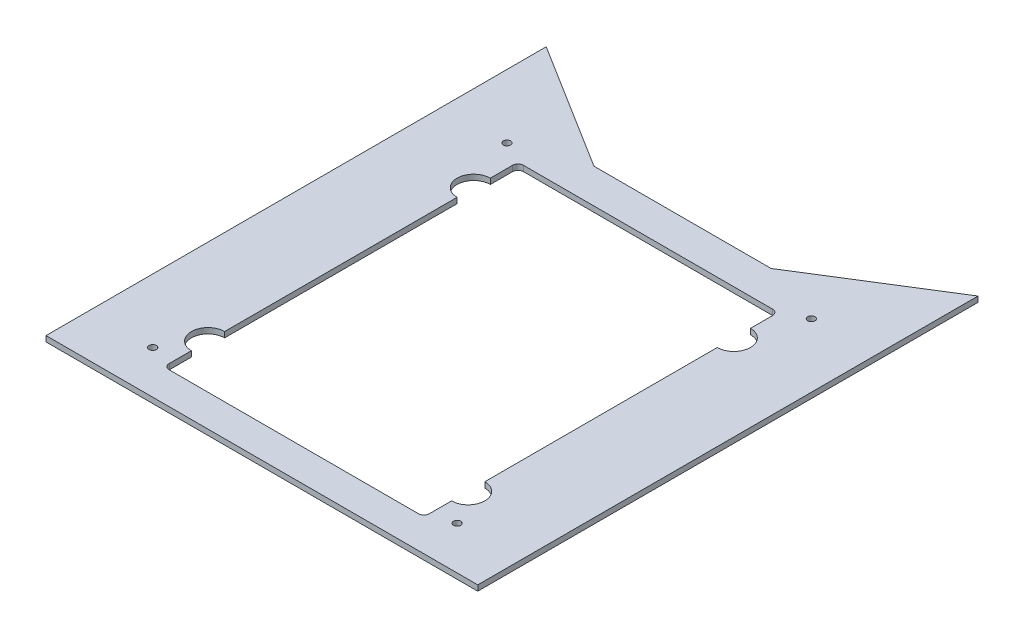
SolidWorks part; units mm, degrees
material "Balsa"
ref_plane "Front Plane" through (0, 0, 0) normal (0, 0, 1) x (1, 0, 0)
ref_plane "Top Plane" through (0, 0, 0) normal (0, 1, 0) x (1, 0, 0)
ref_plane "Right Plane" through (0, 0, 0) normal (1, 0, 0) x (0, 0, -1)
sketch "Sketch1" plane through (0, 0, 0) normal (0, 1, 0) x (1, 0, 0)
  line L17 (265.3132, -148.5502) -> (201.8132, -148.5502) construction
  line L18 (265.3132, -148.5502) -> (265.3132, -339.0502) construction
  line L19 (265.3132, -339.0502) -> (201.8132, -339.0502) construction
  line L20 (201.8132, -148.5502) -> (201.8132, -339.0502) construction
  line L21 (-153.7868, -148.5502) -> (-153.7868, -339.0502) construction
  line L22 (-217.2868, -339.0502) -> (-153.7868, -339.0502) construction
  line L23 (-217.2868, -148.5502) -> (-217.2868, -339.0502) construction
  line L24 (-217.2868, -148.5502) -> (-153.7868, -148.5502) construction
  line L25 (-242.6868, -133.4325) -> (-242.6868, -385.4912) construction
  line L26 (-191.8868, -438.1717) -> (-242.6868, -387.3717) construction
  line L27 (-191.8868, -438.1717) -> (239.9132, -438.1717) construction
  line L28 (239.9132, -438.1717) -> (290.7132, -387.3717) construction
  line L29 (290.7132, -387.3717) -> (290.7132, -133.3717) construction
  line L30 (290.7132, -133.3717) -> (176.4132, -82.5717) construction
  line L31 (176.4132, -82.5717) -> (176.4132, -133.3717) construction
  line L32 (176.4132, -133.3717) -> (74.8132, -196.8717) construction
  line L33 (74.8132, -196.8717) -> (-26.7868, -196.8717) construction
  line L34 (-128.3868, -133.3717) -> (-26.7868, -196.8717) construction
  line L35 (-128.3868, -82.5717) -> (-128.3868, -133.3717) construction
  line L36 (-242.6868, -133.3717) -> (-128.3868, -82.5717) construction
  line L37 (265.3132, -148.5502) -> (201.8132, -148.5502)
  line L38 (265.3132, -148.5502) -> (265.3132, -339.0502)
  line L39 (265.3132, -339.0502) -> (201.8132, -339.0502)
  line L40 (201.8132, -148.5502) -> (201.8132, -339.0502)
  line L41 (-153.7868, -148.5502) -> (-153.7868, -339.0502)
  line L42 (-217.2868, -339.0502) -> (-153.7868, -339.0502)
  line L43 (-217.2868, -148.5502) -> (-217.2868, -339.0502)
  line L44 (-217.2868, -148.5502) -> (-153.7868, -148.5502)
  line L45 (-242.6868, -133.4325) -> (-242.6868, -385.4912)
  line L46 (-191.8868, -438.1717) -> (-242.6868, -387.3717)
  line L47 (-191.8868, -438.1717) -> (239.9132, -438.1717)
  line L48 (239.9132, -438.1717) -> (290.7132, -387.3717)
  line L49 (290.7132, -387.3717) -> (290.7132, -133.3717)
  line L50 (290.7132, -133.3717) -> (176.4132, -82.5717)
  line L51 (176.4132, -82.5717) -> (176.4132, -133.3717)
  line L52 (176.4132, -133.3717) -> (74.8132, -196.8717)
  line L53 (74.8132, -196.8717) -> (-26.7868, -196.8717)
  line L54 (-128.3868, -133.3717) -> (-26.7868, -196.8717)
  line L55 (-128.3868, -82.5717) -> (-128.3868, -133.3717)
  line L56 (-242.6868, -133.3717) -> (-128.3868, -82.5717)
  line L57 (-242.6868, -133.4325) -> (-242.6868, -133.3717)
  line L58 (-242.6868, -385.4912) -> (-242.6868, -387.3717)
extrude "Boss-Extrude1" add sketch "Sketch1" along normal blind 3.175
sketch "Sketch3" plane through (0, 0, 0) normal (0, 1, 0) x (1, 0, 0)
  line L1 (-143.449, -203.465) -> (-143.449, -284.1354) construction
  line L2 (-143.449, -243.8002) -> (24.0132, -243.8002) construction
  line L3 (-191.8868, -438.1717) -> (239.9132, -438.1717) construction
  line L4 (-217.2868, -339.0502) -> (-153.7868, -339.0502) construction
  point P7 (24.0132, -438.1717)
  line B0 (24.0132, -13.4981) -> (24.0132, 49986.5019) construction
  circle B1 centre (-114.2782, -270.1255) radius 2.0828
  circle B2 centre (-143.449, -284.1354) radius 2.0828
  circle B3 centre (-114.2782, -217.4749) radius 2.0828
  circle B4 centre (-143.449, -203.465) radius 2.0828
  circle B5 centre (191.4754, -284.1354) radius 2.0828
  circle B6 centre (162.3046, -270.1255) radius 2.0828
  circle B7 centre (162.3046, -217.4749) radius 2.0828
  circle B8 centre (191.4754, -203.465) radius 2.0828
  dimension "D1" = 95.25
sketch_block_instance "motor_mount_pattern-1"
sketch_block "motor_mount_pattern"
extrude "Cut-Extrude2" cut sketch "Sketch3" along normal through all
sketch "Sketch4" plane through (0, 0, 0) normal (0, 1, 0) x (1, 0, 0)
  line L0 (24.0132, -54.7802) -> (24.0132, -50054.7802) construction
  line L1 (24.0132, -200460.6227) -> (24.0132, 249539.3773) construction
  circle A0 centre (111.3257, -210.2986) radius 2.0828
  circle A1 centre (111.3257, -413.4986) radius 2.0828
  circle A2 centre (-63.2993, -413.4986) radius 2.0828
  circle A3 centre (-63.2993, -210.2986) radius 2.0828
  line B0 (-50.5993, -216.6486) -> (98.6257, -216.6486)
  line B1 (-50.5993, -216.6486) -> (-50.5993, -232.5236)
  line B2 (-50.5993, -419.8486) -> (98.6257, -419.8486)
  line B3 (98.6257, -216.6486) -> (98.6257, -232.5236)
  line B4 (-50.5993, -251.5736) -> (-50.5993, -384.9236)
  line B5 (98.6257, -251.5736) -> (98.6257, -384.9236)
  line B6 (-50.5993, -403.9736) -> (-50.5993, -419.8486)
  line B7 (98.6257, -403.9736) -> (98.6257, -419.8486)
  arc B8 (-50.5993, -232.5236) -> (-50.5993, -251.5736) centre (-50.5993, -242.0486) ccw
  arc B9 (98.6257, -251.5736) -> (98.6257, -232.5236) centre (98.6257, -242.0486) ccw
  arc B10 (-50.5993, -384.9236) -> (-50.5993, -403.9736) centre (-50.5993, -394.4486) ccw
  arc B11 (98.6257, -403.9736) -> (98.6257, -384.9236) centre (98.6257, -394.4486) ccw
  dimension "D5" = 4.1656
  dimension "D1" = 12.7
  dimension "D2" = 6.35
  dimension "D3" = 12.7
  dimension "D4" = 6.35
sketch_block_instance "electronics_cutout-1"
sketch_block "electronics_cutout" parameters "D4"=17.1095, "D6"=25.5924, "D1"=203.2, "D2"=149.225, "D3"=35.6511, "D5"=24.7946
extrude "Cut-Extrude4" cut sketch "Sketch4" along normal through all
fillet "Fillet2" radius 3.175 4 edges at (-50.5993, 1.5875, 419.8486) (98.6257, 1.5875, 419.8486) (98.6257, 1.5875, 216.6486) (-50.5993, 1.5875, 216.6486)
sketch "Sketch5" plane through (0, 3.175, 0) normal (0, 1, 0) x (1, 0, 0)
  line L0 (24.0132, -196.8717) -> (24.0132, 49803.1283) construction
  line L1 (74.8132, -196.8717) -> (-26.7868, -196.8717) construction
  line L3 (-191.8868, -438.1717) -> (239.9132, -438.1717) construction
  line L4 (-99.8118, -438.1717) -> (-242.6868, -438.1717)
  line L5 (-242.6868, -438.1717) -> (-242.6868, -82.5717)
  line L6 (-242.6868, -82.5717) -> (-99.8118, -82.5717)
  line L8 (-99.8118, -82.5717) -> (-99.8118, -438.1717)
  line L9 (-242.6868, -133.3717) -> (-242.6868, -387.3717) construction
  line L10 (147.8382, -438.1717) -> (290.7132, -438.1717)
  line L11 (290.7132, -438.1717) -> (290.7132, -82.5717)
  line L12 (147.8382, -82.5717) -> (147.8382, -438.1717)
  line L13 (290.7132, -82.5717) -> (147.8382, -82.5717)
  point P4 (24.0132, -196.8717)
  dimension "D1" = 247.65
extrude "Cut-Extrude5" cut sketch "Sketch5" against normal through all both and the other way through all
